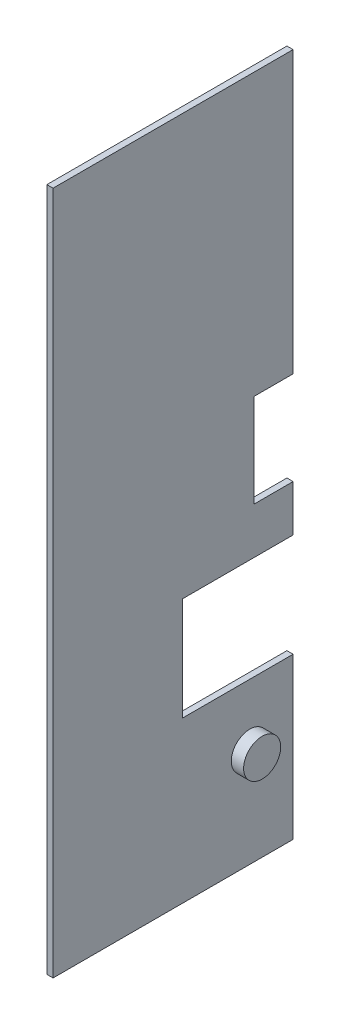
SolidWorks part; units mm, degrees
ref_plane "Спереди" through (0, 0, 0) normal (0, 0, 1) x (1, 0, 0)
ref_plane "Сверху" through (0, 0, 0) normal (0, 1, 0) x (1, 0, 0)
ref_plane "Справа" through (0, 0, 0) normal (1, 0, 0) x (0, 0, -1)
ref_plane "Плоскость4" through (0.5, 0, 0) normal (-1, 0, 0) x (0, -1, 0)
sketch "Эскиз1" plane through (0.5, 0, 0) normal (-1, 0, 0) x (0, -1, 0)
  line L0 (9.85, 42.25) -> (-100.85, 42.25)
  line L1 (-100.85, 42.25) -> (-100.85, 3.4)
  line L2 (-100.85, 3.4) -> (9.85, 3.4)
  line L3 (9.85, 3.4) -> (9.85, 42.25)
extrude "Бобышка-Вытянуть1" add sketch "Эскиз1" against normal blind 0.5
sketch "Эскиз2" plane through (0.5, 0, 0) normal (-1, 0, 0) x (0, 0, 1)
  line L0 (42.25, -9.85) -> (3.4, -9.85)
  line L1 (3.4, -9.85) -> (3.4, 100.85)
  line L2 (3.4, 100.85) -> (42.25, 100.85)
  line L3 (42.25, 100.85) -> (42.25, -9.85)
extrude "Бобышка-Вытянуть2" add sketch "Эскиз2" along normal blind 0.5
sketch "Эскиз3" plane through (0, 0, 0) normal (-1, 0, 0) x (0, 0, 1)
  line L0 (3.4, 100.85) -> (3.4, -9.85) construction
  line L1 (3.4, 32.8159) -> (21.3328, 32.8159)
  line L2 (3.4, 32.8159) -> (3.4, 16.1071)
  line L3 (3.4, 16.1071) -> (21.3328, 16.1071)
  line L4 (21.3328, 32.8159) -> (21.3328, 16.1071)
extrude "Вырез-Вытянуть1" cut sketch "Эскиз3" against normal blind 10
sketch "Эскиз4" plane through (0, 0, 0) normal (-1, 0, 0) x (0, 0, 1)
  line L0 (3.4, 100.85) -> (3.4, 32.8159) construction
  line L1 (3.4, 55.4013) -> (9.7385, 55.4013)
  line L2 (3.4, 55.4013) -> (3.4, 40.3057)
  line L3 (3.4, 40.3057) -> (9.7385, 40.3057)
  line L4 (9.7385, 55.4013) -> (9.7385, 40.3057)
extrude "Вырез-Вытянуть2" cut sketch "Эскиз4" against normal blind 3
sketch "Эскиз5" plane through (0, 0, 0) normal (-1, 0, 0) x (0, 0, 1)
  circle A0 centre (10.4104, 6.11) radius 1.3797
  point P2 (11.2444, 6.7695)
  point P3 (10.3581, 6.0614)
  point P4 (10.4104, 6.11)
extrude "Вырез-Вытянуть3" cut sketch "Эскиз5" against normal blind 3
sketch "Эскиз6" plane through (1, 0, 0) normal (1, 0, 0) x (0, 0, -1)
  circle A0 centre (-10.4104, 6.11) radius 2.2735
  circle A1 centre (-10.4104, 6.11) radius 3
extrude "Бобышка-Вытянуть3" add sketch "Эскиз6" along normal blind 1
sketch "Эскиз7" plane through (2, 0, 0) normal (1, 0, 0) x (0, 0, -1)
  circle A0 centre (-10.4104, 6.11) radius 3
extrude "Бобышка-Вытянуть4" add sketch "Эскиз7" along normal blind 1
